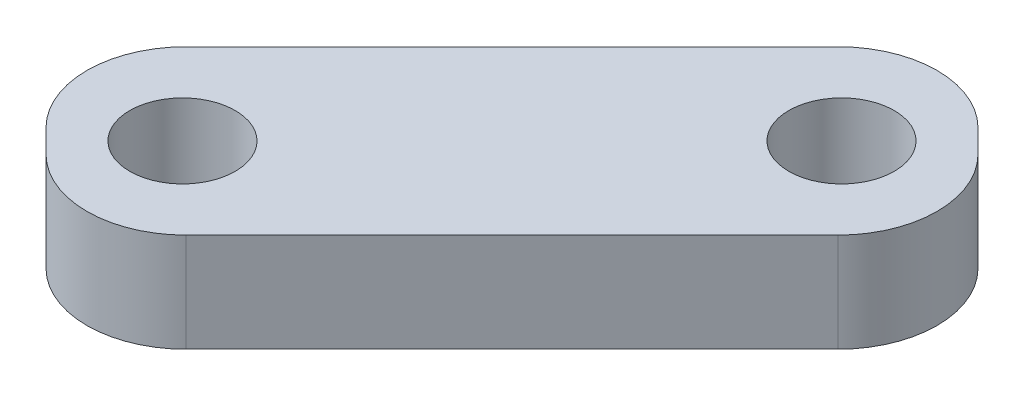
SolidWorks part; units mm, degrees
ref_plane "Alzado" through (0, 0, 0) normal (0, 0, 1) x (1, 0, 0)
ref_plane "Planta" through (0, 0, 0) normal (0, 1, 0) x (1, 0, 0)
ref_plane "Vista lateral" through (0, 0, 0) normal (1, 0, 0) x (0, 0, -1)
sketch "Croquis1" plane through (0, 0, 0) normal (0, 1, 0) x (1, 0, 0)
  line L0 (-5.4038, -5.4038) -> (5.4038, 5.4038) construction
  line L1 (-9.5459, -4.5962) -> (4.5962, 9.5459)
  line L2 (4.5962, 9.5459) -> (9.5459, 4.5962)
  line L3 (9.5459, 4.5962) -> (-4.5962, -9.5459)
  line L4 (-4.5962, -9.5459) -> (-9.5459, -4.5962)
  line L5 (-3.0177, 3.0177) -> (3.0177, -3.0177) construction
  circle A0 centre (-5, -5) radius 1.6
  circle A1 centre (5, 5) radius 1.6
  point P2 (7.0711, 7.0711)
  point P11 (-7.0711, -7.0711)
  point P15 (-2.0829, 1.974)
  point P16 (-3.7656, 3.7656)
  point P18 (-2.4749, 2.4749)
  point P19 (-10.2939, -3.7656)
  point P20 (0, 0)
  point P21 (-4.5962, -4.5962)
  point P22 (-4.5962, -4.5962)
  dimension "D2" = 10
  dimension "D1" = 10
  dimension "D3" = 3.2
  dimension "D4" = 7
  dimension "D5" = 20
  dimension "D6" = 5
extrude "Saliente-Extruir1" add sketch "Croquis1" along normal blind 3
fillet "Redondeo1" radius 3 4 edges at (9.5459, 1.5, -4.5962) (-4.5962, 1.5, 9.5459) (-9.5459, 1.5, 4.5962) (4.5962, 1.5, -9.5459)
